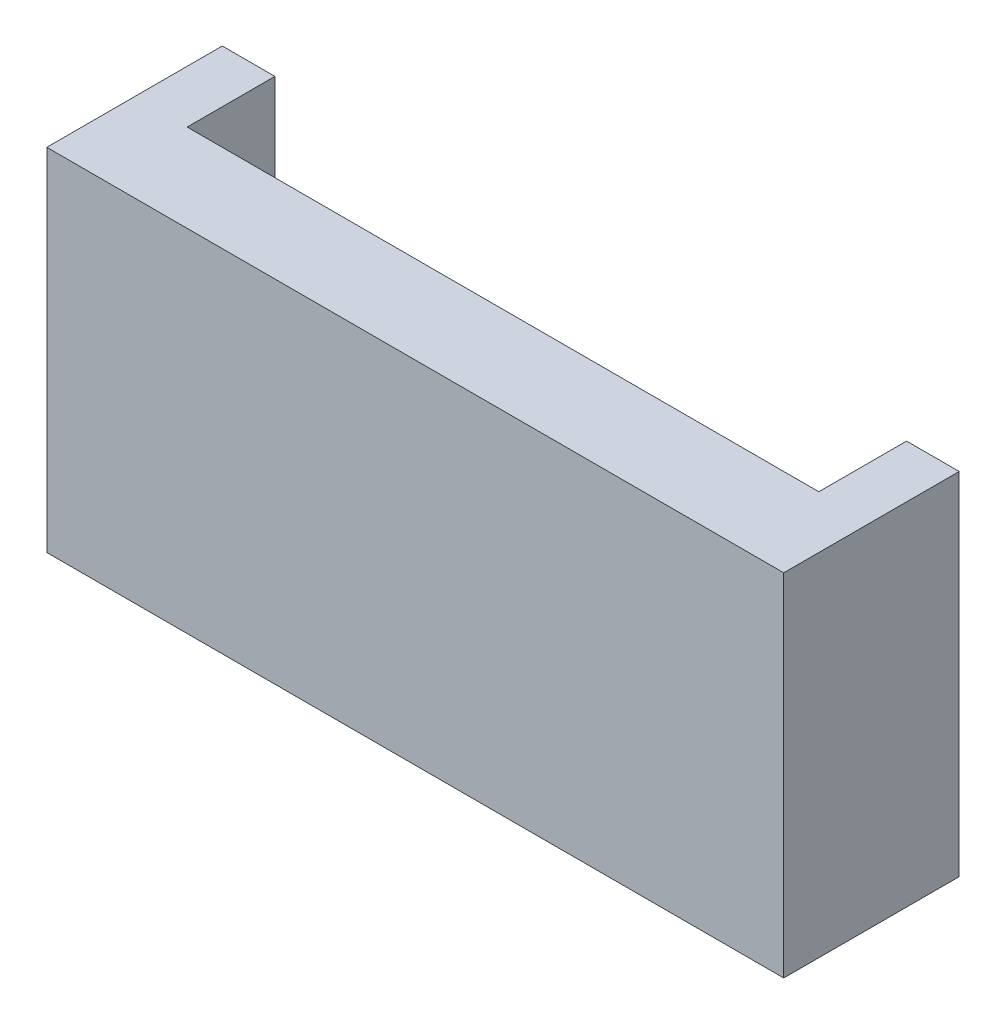
SolidWorks part; units mm, degrees
ref_plane "Front Plane" through (0, 0, 0) normal (0, 0, 1) x (1, 0, 0)
ref_plane "Top Plane" through (0, 0, 0) normal (0, 1, 0) x (1, 0, 0)
ref_plane "Right Plane" through (0, 0, 0) normal (1, 0, 0) x (0, 0, -1)
sketch "Sketch1" plane through (0, 0, 0) normal (0, 1, 0) x (1, 0, 0)
  line L1 (-5.8482, 2.6116) -> (12.1518, 2.6116)
  line L2 (-5.8482, 2.6116) -> (-5.8482, -2.3884)
  line L3 (-5.8482, -2.3884) -> (12.1518, -2.3884)
  line L4 (12.1518, 2.6116) -> (12.1518, -2.3884)
  dimension "D1" = 5
  dimension "D2" = 18
extrude "Boss-Extrude1" add sketch "Sketch1" along normal blind 1.5
sketch "Sketch2" plane through (0, 1.5, 0) normal (0, 1, 0) x (1, 0, 0)
  line L1 (12.1518, -2.3884) -> (12.1518, 2.6116) construction
  line L2 (-5.8482, -2.3884) -> (12.1518, -2.3884)
  line L3 (-5.8482, -2.3884) -> (-5.8482, 0.1116)
  line L4 (-5.8482, 0.1116) -> (12.1518, 0.1116)
  line L5 (12.1518, -2.3884) -> (12.1518, 0.1116)
  line L6 (-5.8482, 0.1116) -> (-5.8482, 1.6116) construction
  line L7 (-5.8482, 2.6116) -> (-5.8482, -2.3884) construction
  line L8 (12.1518, 2.6116) -> (-5.8482, 2.6116) construction
  line L9 (-5.8482, 1.6116) -> (-1.0482, 1.6116)
  line L10 (-5.8482, 1.6116) -> (-5.8482, 2.6116)
  line L11 (-5.8482, 2.6116) -> (-1.0482, 2.6116)
  line L12 (-1.0482, 1.6116) -> (-1.0482, 2.6116)
  line L14 (12.1518, 1.6116) -> (7.3518, 1.6116)
  line L15 (12.1518, 1.6116) -> (12.1518, 2.6116)
  line L16 (12.1518, 2.6116) -> (7.3518, 2.6116)
  line L17 (7.3518, 1.6116) -> (7.3518, 2.6116)
  dimension "D1" = 2.5
  dimension "D2" = 4.8
  dimension "D3" = 4.8
  dimension "D4" = 1
  dimension "D5" = 1
extrude "Boss-Extrude3" add sketch "Sketch2" along normal blind 4
sketch "Sketch4" plane through (0, 5.5, 0) normal (0, 1, 0) x (1, 0, 0)
  line L1 (12.1518, -2.3884) -> (-5.8482, -2.3884)
  line L2 (12.1518, -2.3884) -> (12.1518, 0.1116)
  line L3 (12.1518, 0.1116) -> (-5.8482, 0.1116)
  line L4 (-5.8482, -2.3884) -> (-5.8482, 0.1116)
extrude "Boss-Extrude4" add sketch "Sketch4" along normal blind 4.5
sketch "Sketch6" plane through (12.1518, 0, 0) normal (1, 0, 0) x (0, 0, -1)
  line L1 (-2.3884, 0) -> (2.6116, 0)
  line L2 (-2.3884, 0) -> (-2.3884, 10)
  line L3 (-2.3884, 10) -> (2.6116, 10)
  line L4 (2.6116, 0) -> (2.6116, 10)
  dimension "D1" = 10
  dimension "D2" = 5
extrude "Boss-Extrude5" add sketch "Sketch6" along normal blind 1.5
sketch "Sketch7" plane through (-5.8482, 0, 0) normal (-1, 0, 0) x (0, 0, 1)
  line L1 (2.3884, 0) -> (-2.6116, 0)
  line L2 (2.3884, 0) -> (2.3884, 10)
  line L3 (2.3884, 10) -> (-2.6116, 10)
  line L4 (-2.6116, 0) -> (-2.6116, 10)
extrude "Boss-Extrude6" add sketch "Sketch7" along normal blind 1.5
